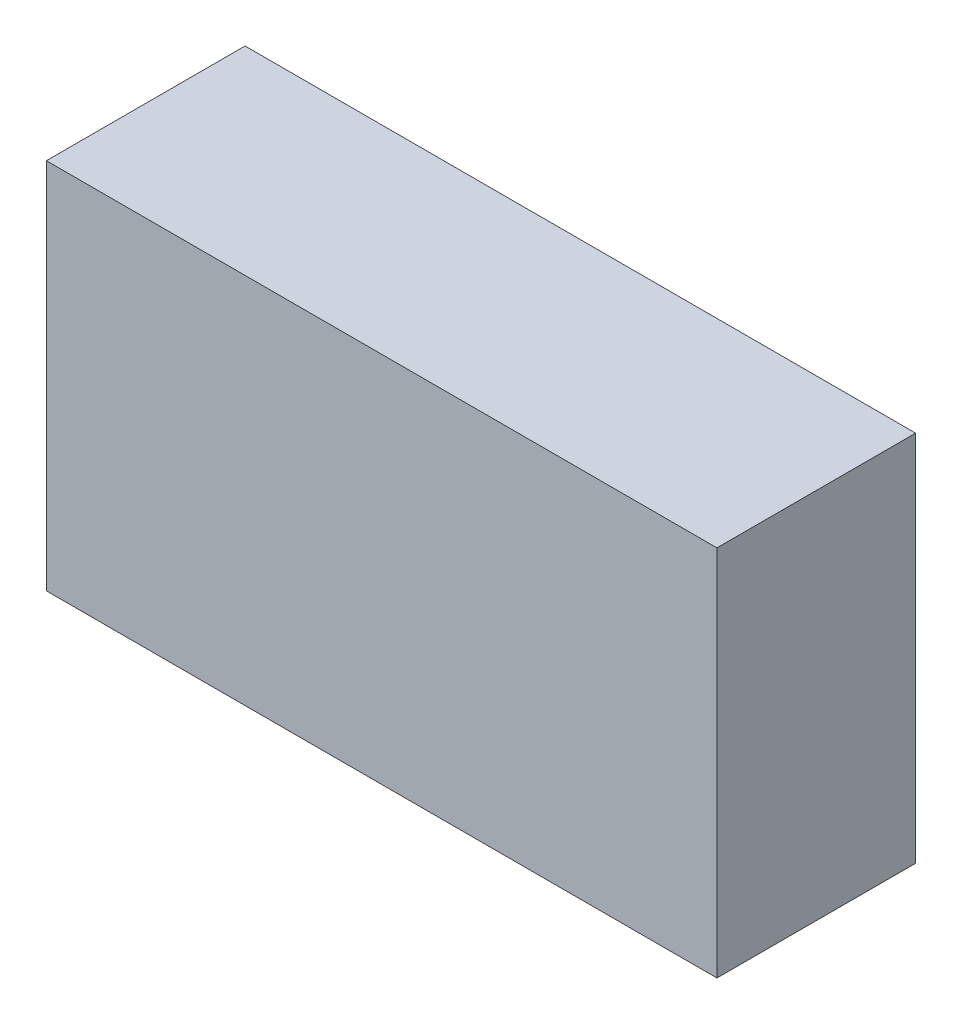
SolidWorks part; units mm, degrees
ref_plane "Front Plane" through (0, 0, 0) normal (0, 0, 1) x (1, 0, 0)
ref_plane "Top Plane" through (0, 0, 0) normal (0, 1, 0) x (1, 0, 0)
ref_plane "Right Plane" through (0, 0, 0) normal (1, 0, 0) x (0, 0, -1)
sketch "Sketch1" plane through (0, 0, 0) normal (0, 0, 1) x (1, 0, 0)
  line L1 (27, -15) -> (-27, -15)
  line L2 (27, -15) -> (27, 15)
  line L3 (27, 15) -> (-27, 15)
  line L4 (-27, -15) -> (-27, 15)
  line L5 (27, -15) -> (-27, 15) construction
  line L6 (27, 15) -> (-27, -15) construction
  point P0 (0, 0)
  dimension "D1" = 30
  dimension "D2" = 54
extrude "Boss-Extrude1" add sketch "Sketch1" along normal blind 16
sketch "Sketch2" plane through (0, 0, 0) normal (0, 0, -1) x (-1, 0, 0)
  text T0 "7.4V\r\n1000mAh"
extrude "Boss-Extrude2" add sketch "Sketch2" along normal blind 0.5
